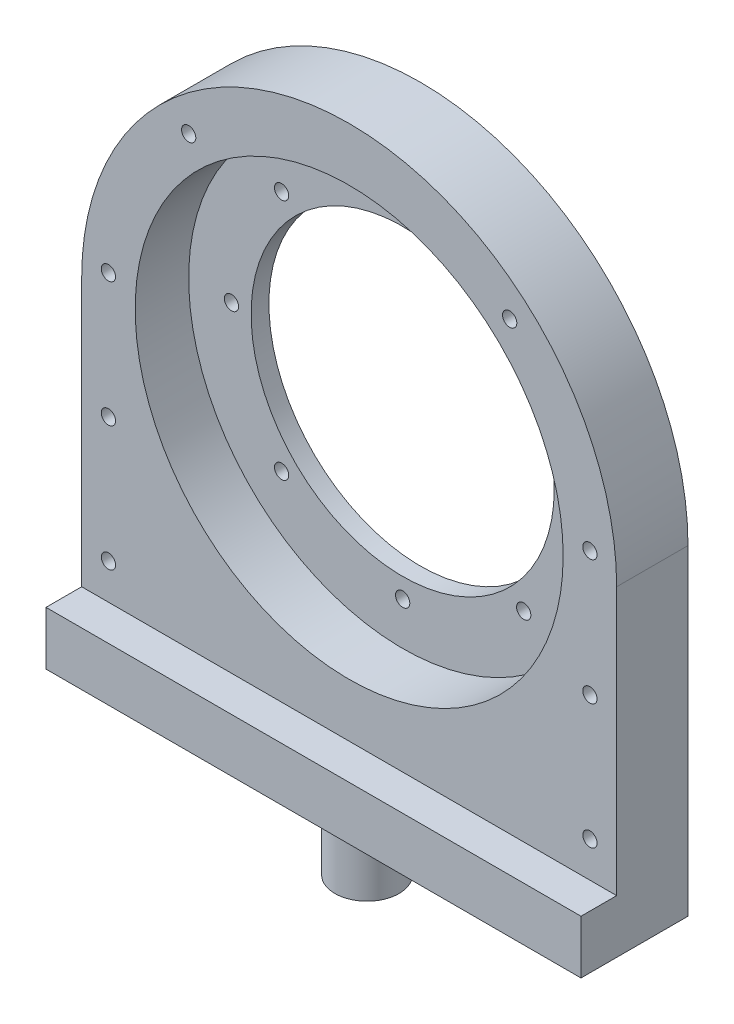
SolidWorks part; units mm, degrees
ref_plane "Front Plane" through (0, 0, 0) normal (0, 0, 1) x (1, 0, 0)
ref_plane "Top Plane" through (0, 0, 0) normal (0, 1, 0) x (1, 0, 0)
ref_plane "Right Plane" through (0, 0, 0) normal (1, 0, 0) x (0, 0, -1)
sketch "Sketch1" plane through (0, 0, 0) normal (1, 0, 0) x (0, 0, -1)
  line L1 (-21.7185, 0) -> (8.2815, 0)
  line L2 (-21.7185, 0) -> (-21.7185, -15)
  line L3 (-21.7185, -15) -> (8.2815, -15)
  line L4 (8.2815, 0) -> (8.2815, -15)
  dimension "D1" = 30
  dimension "D2" = 15
extrude "Boss-Extrude1" add sketch "Sketch1" along normal blind 150
sketch "Sketch2" plane through (0, -15, 0) normal (0, -1, 0) x (1, 0, 0)
  line L0 (150, 21.7185) -> (0, 21.7185) construction
  line L2 (0, 21.7185) -> (0, -8.2815) construction
  circle A0 centre (75, 6.7185) radius 12.7
  point P6 (0, 9.2035)
  dimension "D1" = 15
  dimension "D2" = 75
extrude "Cut-Extrude1" cut sketch "Sketch2" against normal blind 5
sketch "Sketch3" plane through (0, -10, 0) normal (0, -1, 0) x (1, 0, 0)
  circle A0 centre (75, 6.7185) radius 9
  circle A1 centre (75, 6.7185) radius 12.7 construction
  dimension "D1" = 0
extrude "Boss-Extrude2" add sketch "Sketch3" along normal blind 25
sketch "Sketch4" plane through (0, 0, 0) normal (0, 1, 0) x (1, 0, 0)
  line L0 (150, 8.2815) -> (150, -21.7185) construction
  line L1 (0, 8.2815) -> (150, 8.2815)
  line L2 (0, 8.2815) -> (0, -11.7185)
  line L3 (0, -11.7185) -> (150, -11.7185)
  line L4 (150, 8.2815) -> (150, -11.7185)
  dimension "D1" = 20
extrude "Boss-Extrude3" add sketch "Sketch4" along normal blind 150
sketch "Sketch5" plane through (0, 0, 11.7185) normal (0, 0, 1) x (1, 0, 0)
  line L0 (150, 150) -> (150, 0) construction
  line L1 (0, 150) -> (150, 150)
  line L2 (0, 150) -> (0, 75)
  line L4 (150, 150) -> (150, 75)
  arc A0 (150, 75) -> (0, 75) centre (75, 75) ccw
  circle A1 centre (75, 75) radius 42.5
  line M2 (150, 0) -> (150, 150)
  line M3 (150, 150) -> (0, 150)
  line M4 (0, 150) -> (0, 0)
extrude "Cut-Extrude2" cut sketch "Sketch5" against normal blind 150 contours A0 L1 M4 | A0 M2 M3 | A1
sketch "Sketch6" plane through (0, 0, 11.7185) normal (0, 0, 1) x (1, 0, 0)
  circle A0 centre (75, 75) radius 60
  circle A1 centre (75, 75) radius 42.5 construction
  point P2 (101.7357, 85.721)
  dimension "D1" = 0
  dimension "D2" = 120
extrude "Cut-Extrude3" cut sketch "Sketch6" against normal blind 15
sketch "Sketch7" plane through (0, 0, -3.2815) normal (0, 0, 1) x (1, 0, 0)
  line L0 (150, 75) -> (150, 0) construction
  circle A0 centre (75, 123) radius 2
  circle A1 centre (75, 75) radius 42.5 construction
  circle A2 centre (108.9411, 108.9411) radius 2
  circle A3 centre (123, 75) radius 2
  circle A4 centre (108.9411, 41.0589) radius 2
  circle A5 centre (75, 27) radius 2
  circle A6 centre (41.0589, 41.0589) radius 2
  circle A7 centre (27, 75) radius 2
  circle A8 centre (41.0589, 108.9411) radius 2
  point P22 (75, 75)
  dimension "D1" = 75
  dimension "D2" = 48
  dimension "D3" = 8
extrude "Cut-Extrude4" cut sketch "Sketch7" against normal blind 15
sketch "Sketch17" plane through (0, 0, 11.7185) normal (0, 0, 1) x (1, 0, 0)
  line L0 (0, 75) -> (0, 0) construction
  line L1 (150, 0) -> (0, 0) construction
  circle A0 centre (7.5, 10) radius 2
  circle A1 centre (142.5, 10) radius 2
  circle A2 centre (142.5, 45) radius 2
  circle A3 centre (142.5, 80) radius 2
  circle A4 centre (7.5, 45) radius 2
  circle A5 centre (7.5, 80) radius 2
  dimension "D1" = 7.5
  dimension "D2" = 10
  dimension "D3" = 2
  dimension "D4" = 3
extrude "Cut-Extrude5" cut sketch "Sketch17" against normal blind 20
sketch "Sketch18" plane through (0, 0, 11.7185) normal (0, 0, 1) x (1, 0, 0)
  line L0 (0, 75) -> (0, 0) construction
  line L1 (150, 0) -> (0, 0) construction
  circle A0 centre (30, 125) radius 2
  circle A1 centre (120, 125) radius 2
  dimension "D1" = 30
  dimension "D2" = 125
  dimension "D3" = 2
extrude "Cut-Extrude6" cut sketch "Sketch18" against normal blind 20
